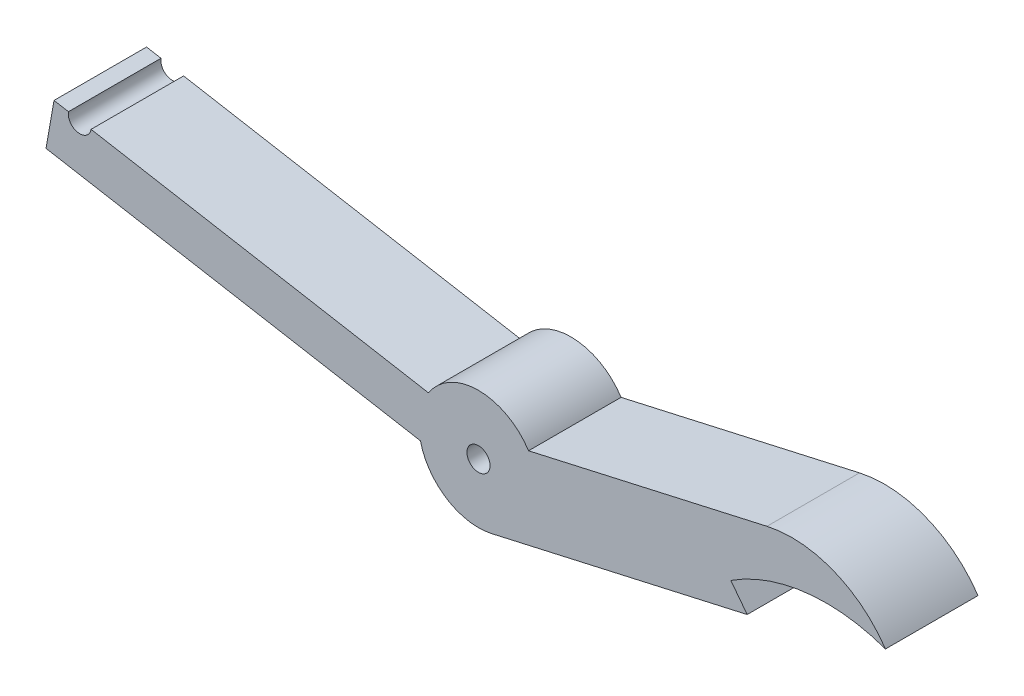
SolidWorks part; units mm, degrees
material "Oak"
ref_plane "Front Plane" through (0, 0, 0) normal (0, 0, 1) x (1, 0, 0)
ref_plane "Top Plane" through (0, 0, 0) normal (0, 1, 0) x (1, 0, 0)
ref_plane "Right Plane" through (0, 0, 0) normal (1, 0, 0) x (0, 0, -1)
sketch "Sketch1" plane through (0, 0, 0) normal (0, 0, 1) x (1, 0, 0)
  line L0 (0, 0) -> (50.8, 0) construction
  line L1 (0, 0) -> (47.7364, -17.3746) construction
  line L2 (34.6352, 2.889) -> (36.8811, -0.0471) construction
  line L3 (61.6179, -32.3874) -> (63.8638, -35.3235) construction
  line L4 (-6.858, 4.4332) -> (-53.1755, 12.6003)
  line L5 (1.7669, -7.9727) -> (36.8811, -0.0471)
  line L6 (36.8811, -0.0471) -> (34.6352, 2.889)
  line L7 (6.8698, 4.4149) -> (39.5958, 11.8014)
  line L8 (0, 0) -> (-42.9058, 0) construction
  line L9 (-7.9606, -1.8203) -> (-59.36, 7.2428)
  line L10 (-58.2573, 13.4963) -> (-59.36, 7.2428)
  line L11 (-56.2773, 13.1472) -> (-58.2573, 13.4963)
  line L12 (-58.8087, 10.3696) -> (0, 0) construction
  circle A0 centre (0, 0) radius 50.8 construction
  circle A1 centre (47.7364, -17.3746) radius 16.6688 construction
  arc A2 (63.8638, -35.3235) -> (34.6352, 2.889) centre (47.7364, -17.3746) ccw construction
  arc A3 (61.6179, -32.3874) -> (36.8811, -0.0471) centre (47.7364, -17.3746) ccw construction
  circle A4 centre (0, 0) radius 1.5875
  arc A5 (6.8698, 4.4149) -> (-6.858, 4.4332) centre (0, 0) ccw
  arc A6 (39.5958, 11.8014) -> (55.8608, 5.3465) centre (43.0086, -3.319) cw
  arc A7 (-56.2773, 13.1472) -> (-53.1755, 12.6003) centre (-54.7264, 12.8737) ccw
  arc A8 (-7.9606, -1.8203) -> (1.7669, -7.9727) centre (0, 0) ccw
  arc A9 (34.6352, 2.889) -> (55.8608, 5.3465) centre (47.7364, -17.3746) cw
  point P6 (66.9025, -2.7146)
  dimension "D3" = 33.3375
  dimension "D4" = 48.26
  dimension "D5" = 40.894
  dimension "D9" = 1.5748
  dimension "D11" = 3.175
  dimension "D12" = 8.1661
  dimension "D13" = 24.13
  dimension "D14" = 15.5007
  dimension "D1" = 50.8
  dimension "D2" = 20
  dimension "D6" = 22.225
  dimension "D7" = 10
  dimension "D8" = 6.35
  dimension "D10" = 3.5854
  dimension "D15" = 12.719
  dimension "D16" = 115.2208
extrude "Boss-Extrude1" add sketch "Sketch1" along normal mid plane 12.7
